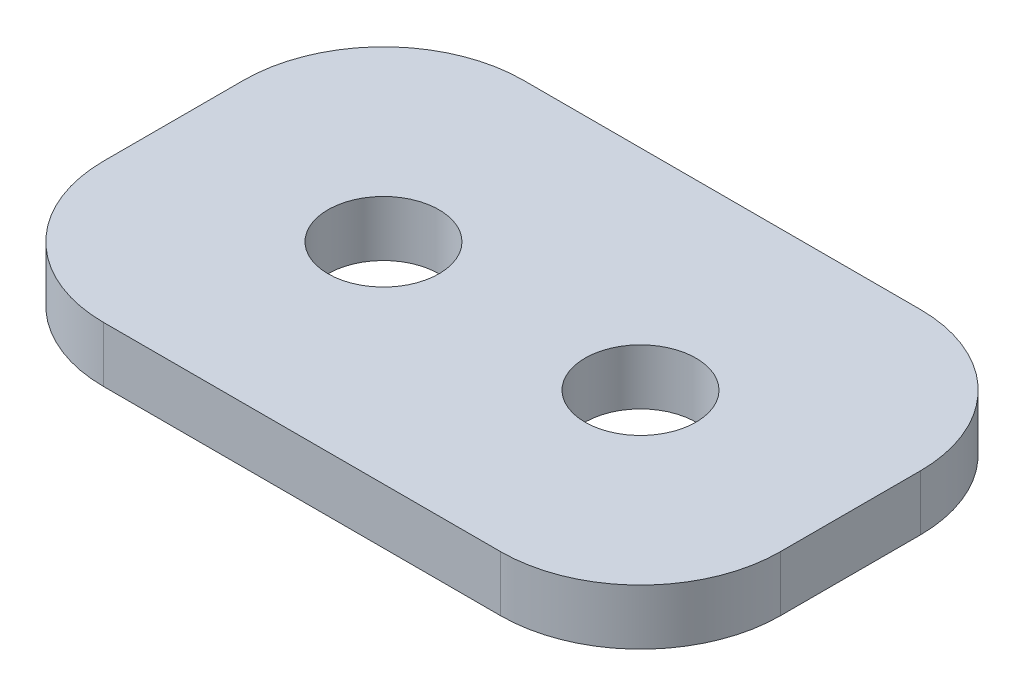
SolidWorks part; units mm, degrees
ref_plane "Front Plane" through (0, 0, 0) normal (0, 0, 1) x (1, 0, 0)
ref_plane "Top Plane" through (0, 0, 0) normal (0, 1, 0) x (1, 0, 0)
ref_plane "Right Plane" through (0, 0, 0) normal (1, 0, 0) x (0, 0, -1)
sketch "Sketch1" plane through (0, 0, 0) normal (0, 1, 0) x (1, 0, 0)
  line L0 (-3.675, 0) -> (3.675, 0) construction
  line L1 (9.675, -6) -> (-9.675, -6)
  line L2 (9.675, -6) -> (9.675, 6)
  line L3 (9.675, 6) -> (-9.675, 6)
  line L4 (-9.675, -6) -> (-9.675, 6)
  line L5 (9.675, -6) -> (-9.675, 6) construction
  line L6 (9.675, 6) -> (-9.675, -6) construction
  circle A0 centre (-3.675, 0) radius 1.5875
  circle A1 centre (3.675, 0) radius 1.5875
  circle A2 centre (-3.675, 0) radius 5 construction
  point P0 (0, 0)
  point P8 (0, 0)
  dimension "D1" = 3.175
  dimension "D4" = 10
  dimension "D2" = 7.35
  dimension "D3" = 12
  dimension "D5" = 6
extrude "Boss-Extrude1" add sketch "Sketch1" along normal mid plane 1.5875
fillet "Fillet1" radius 4 4 edges at (-9.675, 0, -6) (-9.675, 0, 6) (9.675, 0, -6) (9.675, 0, 6)
